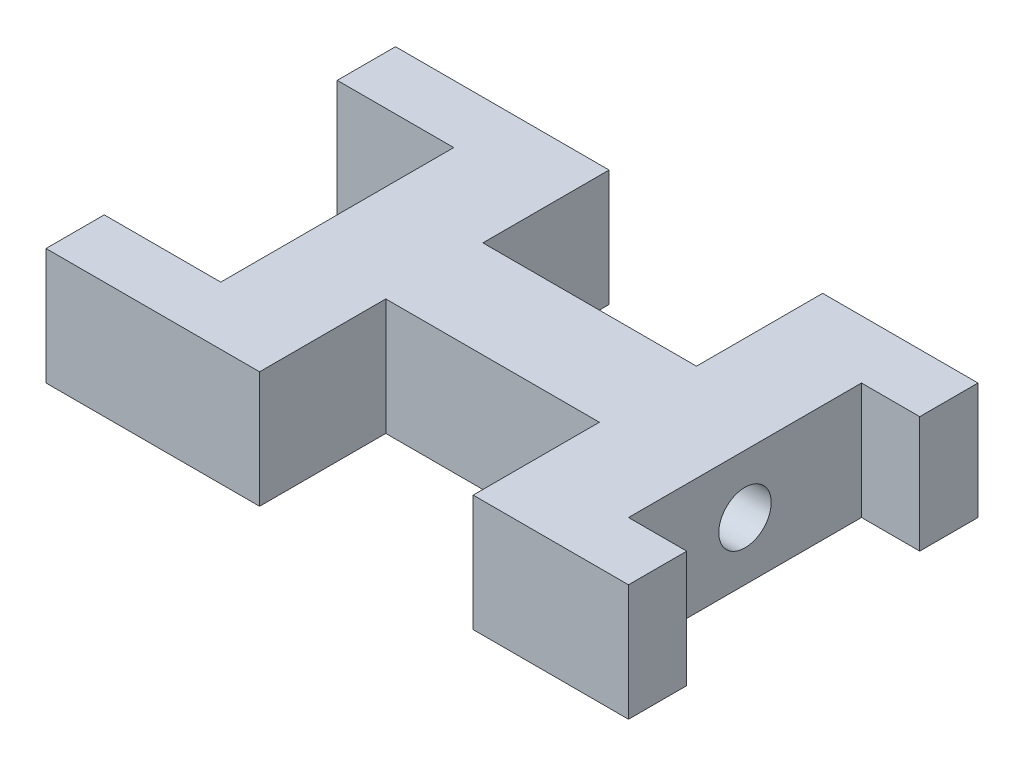
SolidWorks part; units mm, degrees
ref_plane "Front Plane" through (0, 0, 0) normal (0, 0, 1) x (1, 0, 0)
ref_plane "Top Plane" through (0, 0, 0) normal (0, 1, 0) x (1, 0, 0)
ref_plane "Right Plane" through (0, 0, 0) normal (1, 0, 0) x (0, 0, -1)
sketch "Sketch1" plane through (0, 0, 0) normal (0, 1, 0) x (1, 0, 0)
  line L0 (10.5, 0) -> (5.5, 0)
  line L1 (-5.5, 9) -> (-5.5, 2.5)
  line L2 (-5.5, -9) -> (-16.5, -9)
  line L3 (-16.5, -9) -> (-16.5, -6)
  line L4 (-16.5, -6) -> (-10.5, -6)
  line L5 (-10.5, -6) -> (-10.5, 0)
  line L6 (-5.5, 9) -> (-16.5, 9)
  line L7 (-16.5, 9) -> (-16.5, 6)
  line L8 (-16.5, 6) -> (-10.5, 6)
  line L9 (-10.5, 6) -> (-10.5, 1.8478)
  line L11 (5.5, 2.5) -> (-5.5, 2.5)
  line L12 (5.5, -2.5) -> (-5.5, -2.5)
  line L13 (5.5, 9) -> (5.5, 2.5)
  line L14 (5.5, -9) -> (10.5, -9)
  line L15 (10.5, -6) -> (10.5, 6)
  line L16 (10.5, 9) -> (5.5, 9)
  line L17 (10.5, 9) -> (13.5, 9)
  line L18 (13.5, 9) -> (13.5, 6)
  line L19 (13.5, 6) -> (10.5, 6)
  line L20 (10.5, -9) -> (13.5, -9)
  line L21 (13.5, -9) -> (13.5, -6)
  line L22 (13.5, -6) -> (10.5, -6)
  line L23 (-10.5, 1.8478) -> (-10.5, 0)
  line L24 (-5.5, 0) -> (-10.5, 0)
  line L25 (-5.5, -2.5) -> (-5.5, -9)
  line L26 (5.5, -2.5) -> (5.5, -9)
  point P4 (0, 0)
  point P8 (-10.5, 0)
  point P9 (-10.5, 0)
  point P18 (0, 0)
  point P21 (0, 2.5)
  point P24 (0, -2.5)
  point P27 (5.5, 0)
  dimension "D1" = 21
  dimension "D2" = 18
  dimension "D3" = 5
  dimension "D4" = 6
  dimension "D5" = 3
  dimension "D6" = 3
  dimension "D8" = 3
  dimension "D9" = 3
extrude "Boss-Extrude1" add sketch "Sketch1" along normal blind 6
sketch "Sketch2" plane through (10.5, 0, 0) normal (1, 0, 0) x (0, 0, -1)
  line L0 (0, 6) -> (0, 0) construction
  line L1 (-6, 6) -> (6, 6) construction
  line L2 (-6, 0) -> (6, 0) construction
  circle A0 centre (0, 3) radius 1.35
  dimension "D1" = 2.7
extrude "Cut-Extrude1" cut sketch "Sketch2" against normal through all
